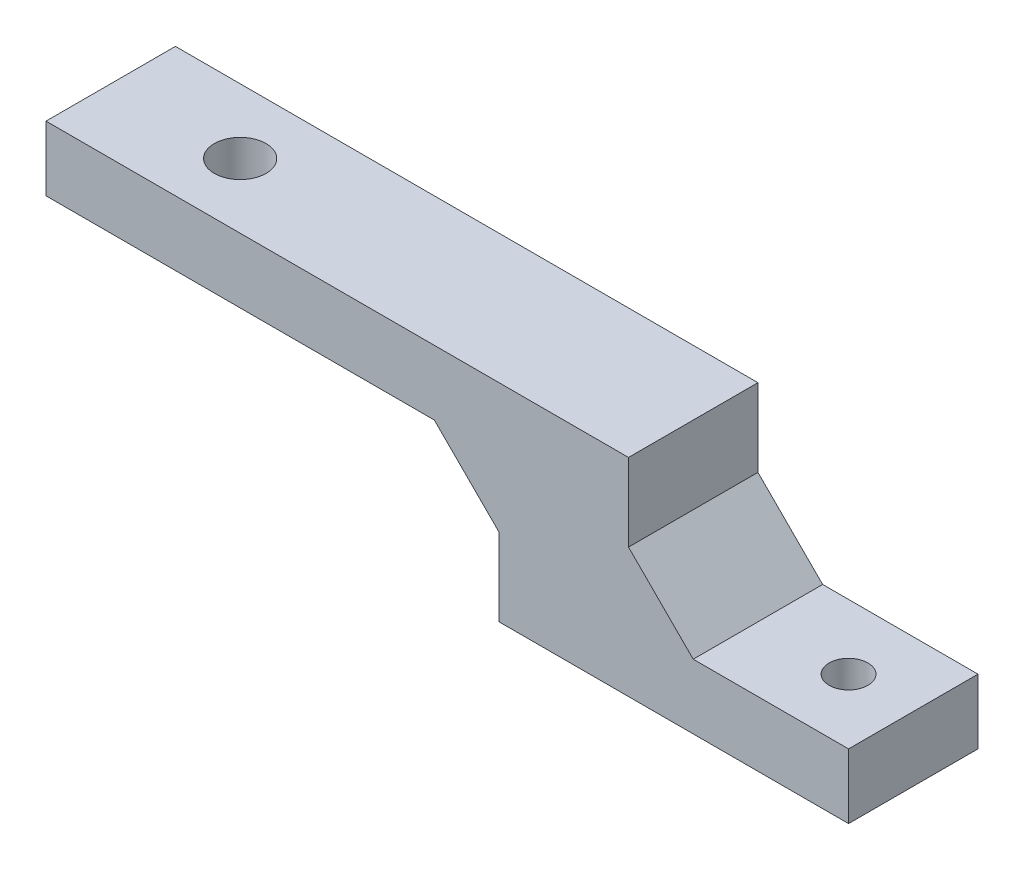
SolidWorks part; units mm, degrees
ref_plane "前视基准面" through (0, 0, 0) normal (0, 0, 1) x (1, 0, 0)
ref_plane "上视基准面" through (0, 0, 0) normal (0, 1, 0) x (1, 0, 0)
ref_plane "右视基准面" through (0, 0, 0) normal (1, 0, 0) x (0, 0, -1)
sketch "草图1" plane through (0, 0, 0) normal (0, 0, 1) x (1, 0, 0)
  line L0 (0, 0) -> (35, 0)
  line L1 (0, 0) -> (0, 5)
  line L2 (0, 5) -> (45, 5)
  line L3 (45, 5) -> (45, -6)
  line L4 (45, -6) -> (62, -6)
  line L5 (62, -6) -> (62, -11)
  line L6 (62, -11) -> (35, -11)
  line L7 (35, -11) -> (35, 0)
  dimension "D1" = 5
  dimension "D2" = 5
  dimension "D3" = 11
  dimension "D4" = 10
  dimension "D5" = 35
  dimension "D6" = 27
extrude "凸台-拉伸1" add sketch "草图1" along normal blind 10
sketch "草图3" plane through (0, -11, 0) normal (0, -1, 0) x (1, 0, 0)
  line L0 (0, 10) -> (0, 0) construction
  line L1 (62, 10) -> (62, 0) construction
  circle A0 centre (10, 5) radius 2
  circle A1 centre (57, 5) radius 1.5
  point P8 (0, 5)
  dimension "D3" = 4
  dimension "D4" = 3
  dimension "D1" = 10
  dimension "D2" = 5
extrude "切除-拉伸1" cut sketch "草图3" against normal blind 30
chamfer "倒角1" distance 5 angle 45 2 edges at (35, 0, 5) (45, -6, 5)
